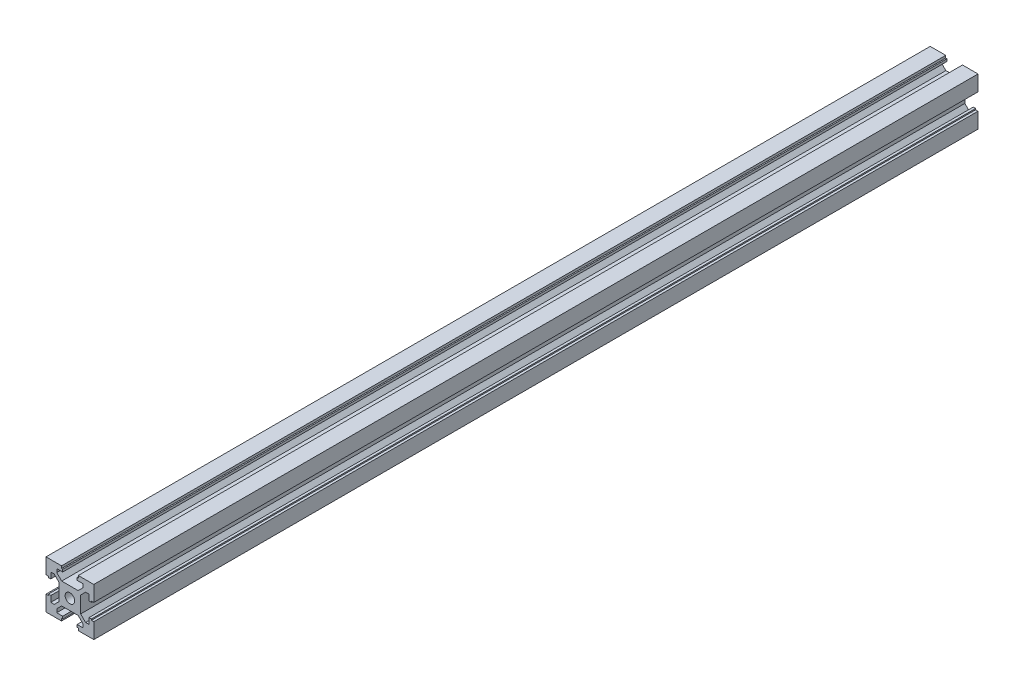
SolidWorks part; units mm, degrees
ref_plane "Front Plane" through (0, 0, 0) normal (0, 0, 1) x (1, 0, 0)
ref_plane "Top Plane" through (0, 0, 0) normal (0, 1, 0) x (1, 0, 0)
ref_plane "Right Plane" through (0, 0, 0) normal (1, 0, 0) x (0, 0, -1)
sketch "Sketch1" plane through (0, 0, 0) normal (0, 0, 1) x (1, 0, 0)
  line L0 (0, 10) -> (0, -4.5007) construction
  line L1 (-10, -10) -> (-3.5, -10)
  line L2 (-10, -10) -> (-10, -3.5)
  line L3 (-10, 10) -> (-3.5, 10)
  line L4 (10, -10) -> (10, -3.5)
  line L5 (-10, -10) -> (10, 10) construction
  line L6 (-10, 10) -> (10, -10) construction
  line L7 (-10, 0) -> (10, 0) construction
  line L8 (-3.5, 10) -> (-3.5, 9)
  line L9 (-3.44, -4.5007) -> (3.44, -4.5007)
  line L10 (-4.5007, -3.44) -> (-4.5007, 3.44)
  line L11 (-3.44, 4.5007) -> (3.44, 4.5007)
  line L12 (4.5007, -3.44) -> (4.5007, 3.44)
  line L13 (-10, -10) -> (10, 10) construction
  line L14 (-10, 10) -> (10, -10) construction
  line L15 (-3.5, 9) -> (-3, 9)
  line L16 (-3, 9) -> (-3, 8)
  line L17 (-3, 8) -> (-5.5, 8)
  line L18 (-5.5, 8) -> (-5.5, 6.5607)
  line L19 (-5.5, 6.5607) -> (-3.44, 4.5007)
  line L20 (3.5, 10) -> (10, 10)
  line L21 (3.5, 9) -> (3, 9)
  line L22 (5.5, 6.5607) -> (3.44, 4.5007)
  line L23 (5.5, 8) -> (5.5, 6.5607)
  line L24 (3, 8) -> (5.5, 8)
  line L25 (3, 9) -> (3, 8)
  line L26 (3.5, 10) -> (3.5, 9)
  line L27 (-3.5, 10) -> (3.5, 10) construction
  line L28 (5.5, -6.5607) -> (3.44, -4.5007)
  line L29 (5.5, -8) -> (5.5, -6.5607)
  line L30 (3, -8) -> (5.5, -8)
  line L31 (3, -9) -> (3, -8)
  line L32 (3.5, -9) -> (3, -9)
  line L33 (3.5, -10) -> (3.5, -9)
  line L34 (-3.5, -9) -> (-3, -9)
  line L35 (-5.5, -6.5607) -> (-3.44, -4.5007)
  line L36 (-5.5, -8) -> (-5.5, -6.5607)
  line L37 (-3, -8) -> (-5.5, -8)
  line L38 (-3, -9) -> (-3, -8)
  line L39 (-3.5, -10) -> (-3.5, -9)
  line L40 (-6.5607, -5.5) -> (-4.5007, -3.44)
  line L41 (-8, -5.5) -> (-6.5607, -5.5)
  line L42 (-8, -3) -> (-8, -5.5)
  line L43 (-10, -3.5) -> (-9, -3.5)
  line L44 (-9, -3) -> (-8, -3)
  line L45 (-9, -3.5) -> (-9, -3)
  line L46 (6.5607, -5.5) -> (4.5007, -3.44)
  line L47 (8, -5.5) -> (6.5607, -5.5)
  line L48 (8, -3) -> (8, -5.5)
  line L49 (9, -3) -> (8, -3)
  line L50 (9, -3.5) -> (9, -3)
  line L51 (10, -3.5) -> (9, -3.5)
  line L52 (-6.5607, 5.5) -> (-4.5007, 3.44)
  line L53 (-8, 5.5) -> (-6.5607, 5.5)
  line L54 (-8, 3) -> (-8, 5.5)
  line L55 (-9, 3) -> (-8, 3)
  line L56 (-9, 3.5) -> (-9, 3)
  line L57 (-10, 3.5) -> (-9, 3.5)
  line L58 (10, 3.5) -> (9, 3.5)
  line L59 (9, 3.5) -> (9, 3)
  line L60 (9, 3) -> (8, 3)
  line L61 (8, 3) -> (8, 5.5)
  line L62 (8, 5.5) -> (6.5607, 5.5)
  line L63 (6.5607, 5.5) -> (4.5007, 3.44)
  line L64 (10, 3.5) -> (10, 10)
  line L65 (-10, 3.5) -> (-10, 10)
  line L66 (-10, 3.5) -> (-10, -3.5) construction
  line L67 (10, 3.5) -> (10, -3.5) construction
  line L68 (3.5, -10) -> (10, -10)
  line L69 (-3.5, -10) -> (3.5, -10) construction
  circle A0 centre (0, 0) radius 2
  point P0 (0, 0)
  point P10 (0, 0)
  dimension "D10" = 4
  dimension "D1" = 20
  dimension "D2" = 14.5007
  dimension "D3" = 0.75
  dimension "D4" = 3.5
  dimension "D5" = 3
  dimension "D6" = 1
  dimension "D7" = 1
  dimension "D8" = 3.44
  dimension "D9" = 5.5
extrude "Boss-Extrude1" add sketch "Sketch1" along normal blind 370
sketch "Sketch2" plane through (0, 10, 0) normal (0, 1, 0) x (1, 0, 0)
  line L0 (0, 0) -> (0, -37.814) construction
  line L1 (3.44, 0) -> (-3.44, 0) construction
  line L5 (-10, -185) -> (10, -185) construction
  line L6 (-10, -370) -> (-10, 0) construction
  line L7 (10, -370) -> (10, 0) construction
  circle A0 centre (0, -15) radius 2
  circle A1 centre (0, -30) radius 2
  circle A2 centre (0, -355) radius 2
  circle A3 centre (0, -340) radius 2
  dimension "D4" = 4
  dimension "D1" = 15
  dimension "D2" = 15
extrude "Cut-Extrude1" cut sketch "Sketch2" against normal blind 27
sketch "Sketch3" plane through (0, -4.5007, 0) normal (0, -1, 0) x (1, 0, 0)
  line L0 (-10, 370) -> (-10, 0) construction
  circle A0 centre (0, 80) radius 2
  circle A1 centre (0, 290) radius 2
  dimension "D1" = 4
  dimension "D2" = 210
  dimension "D3" = 10
  dimension "D4" = 10
  dimension "D5" = 80
extrude "Cut-Extrude2" cut sketch "Sketch3" against normal blind 28
